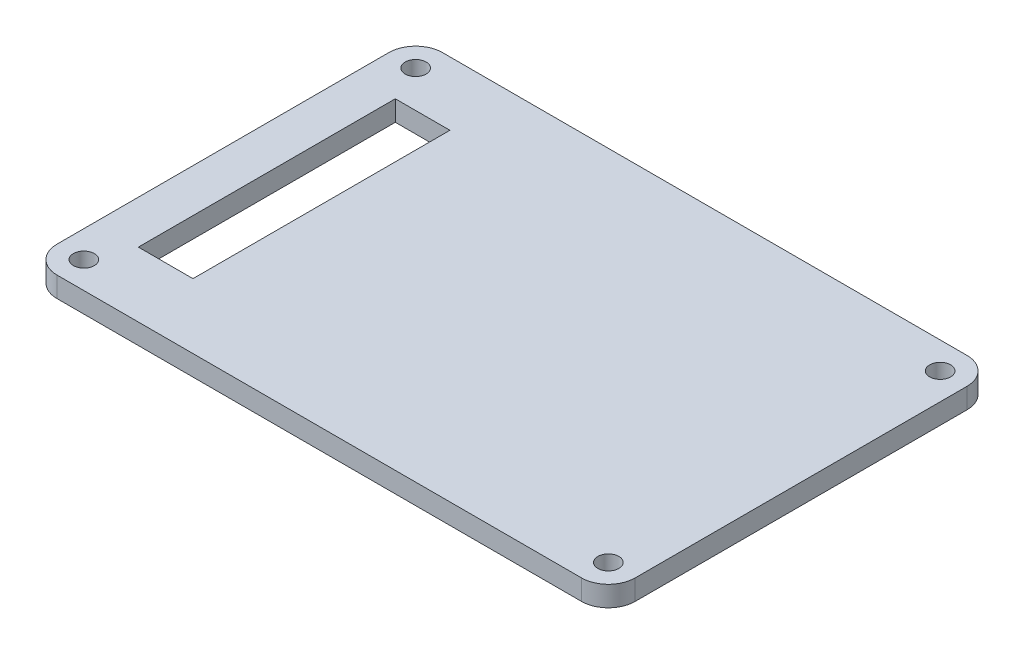
SolidWorks part; units mm, degrees
material "Plain Carbon Steel"
ref_plane "Front" through (0, 0, 0) normal (0, 0, 1) x (1, 0, 0)
ref_plane "Top" through (0, 0, 0) normal (0, 1, 0) x (1, 0, 0)
ref_plane "Right" through (0, 0, 0) normal (1, 0, 0) x (0, 0, -1)
sketch "Sketch1" plane through (0, 0, 0) normal (0, 1, 0) x (1, 0, 0)
  line L0 (-45, 0) -> (45, 0) construction
  line L1 (-45, 30) -> (45, 30) construction
  line L2 (-45, 30) -> (-45, -30) construction
  line L3 (-45, -30) -> (45, -30) construction
  line L4 (45, 30) -> (45, -30) construction
  line L5 (0, -30) -> (0, 30) construction
  line L6 (41.825, 26.825) -> (41.825, -26.825) construction
  line L7 (-41.825, -26.825) -> (41.825, -26.825) construction
  line L8 (-41.825, 26.825) -> (-41.825, -26.825) construction
  line L9 (-41.825, 26.825) -> (41.825, 26.825) construction
  line L10 (40.825, 25.825) -> (40.825, -25.825) construction
  line L11 (-40.825, -25.825) -> (40.825, -25.825) construction
  line L12 (-40.825, 25.825) -> (-40.825, -25.825) construction
  line L13 (-40.825, 25.825) -> (40.825, 25.825) construction
  line L14 (40.825, 21.65) -> (45, 21.65) construction
  line L15 (40.825, -21.65) -> (45, -21.65) construction
  line L16 (36.65, -25.825) -> (36.65, -30) construction
  line L17 (-36.65, -25.825) -> (-36.65, -30) construction
  line L18 (-40.825, -21.65) -> (-45, -21.65) construction
  line L19 (-36.65, 25.825) -> (-36.65, 30) construction
  line L20 (-40.825, 21.65) -> (-45, 21.65) construction
  line L21 (36.65, 25.825) -> (36.65, 30) construction
  line L22 (40.825, -25.825) -> (41.825, -25.825) construction
  circle A0 centre (-40.825, -25.825) radius 1 construction
  circle A1 centre (40.825, -25.825) radius 1 construction
  circle A2 centre (40.825, 25.825) radius 1 construction
  circle A3 centre (-40.825, 25.825) radius 1 construction
  circle A4 centre (40.825, -25.825) radius 4.175 construction
  circle A5 centre (40.825, 25.825) radius 4.175 construction
  circle A6 centre (-40.825, 25.825) radius 4.175 construction
  circle A7 centre (-40.825, -25.825) radius 4.175 construction
  dimension "D1" = 90
  dimension "D2" = 60
  dimension "D4" = 1
  dimension "D3" = 3.175
sketch "Sketch2" plane through (0, 0, 0) normal (0, 1, 0) x (1, 0, 0)
  line L0 (-45, 30) -> (-45, -30) construction
  line L1 (-45, -30) -> (45, -30) construction
  line L2 (45, 30) -> (45, -30) construction
  line L3 (-45, 30) -> (45, 30) construction
  line L16 (-45, 25.825) -> (-45, -25.825)
  line L17 (-40.825, -30) -> (40.825, -30)
  line L18 (45, 25.825) -> (45, -25.825)
  line L19 (-40.825, 30) -> (40.825, 30)
  circle A0 centre (40.825, 25.825) radius 4.175 construction
  circle A2 centre (-40.825, 25.825) radius 4.175 construction
  circle A4 centre (40.825, 25.825) radius 1.6319
  circle A5 centre (40.825, -25.825) radius 1.6319
  arc A6 (45, 25.825) -> (40.825, 30) centre (40.825, 25.825) ccw
  circle A7 centre (-40.825, 25.825) radius 1.6319
  arc A8 (-40.825, 30) -> (-45, 25.825) centre (-40.825, 25.825) ccw
  circle A9 centre (-40.825, -25.825) radius 1.6319
  arc A17 (-45, -25.825) -> (-40.825, -30) centre (-40.825, -25.825) ccw
  arc A18 (40.825, -30) -> (45, -25.825) centre (40.825, -25.825) ccw
  dimension "D1" = 3.2639
  dimension "D2" = 3.2639
  dimension "D3" = 3.2639
  dimension "D4" = 3.2639
extrude "Boss-Extrude3" add sketch "Sketch2" along normal blind 3.175
sketch "Sketch3" plane through (0, 3.175, 0) normal (0, 1, 0) x (1, 0, 0)
  line L0 (-29.7653, -19.9) -> (-29.7653, 20.1) construction
  line L1 (-29.7653, 20.1) -> (-38.2653, 20.1) construction
  line L2 (-38.2653, 20.1) -> (-38.2653, -19.9) construction
  line L3 (-38.2653, -19.9) -> (-29.7653, -19.9) construction
  line L4 (-29.7653, -19.9) -> (-29.7653, 20.1)
  line L5 (-29.7653, 20.1) -> (-38.2653, 20.1)
  line L6 (-38.2653, 20.1) -> (-38.2653, -19.9)
  line L7 (-38.2653, -19.9) -> (-29.7653, -19.9)
extrude "Cut-Extrude1" cut sketch "Sketch3" against normal through all
